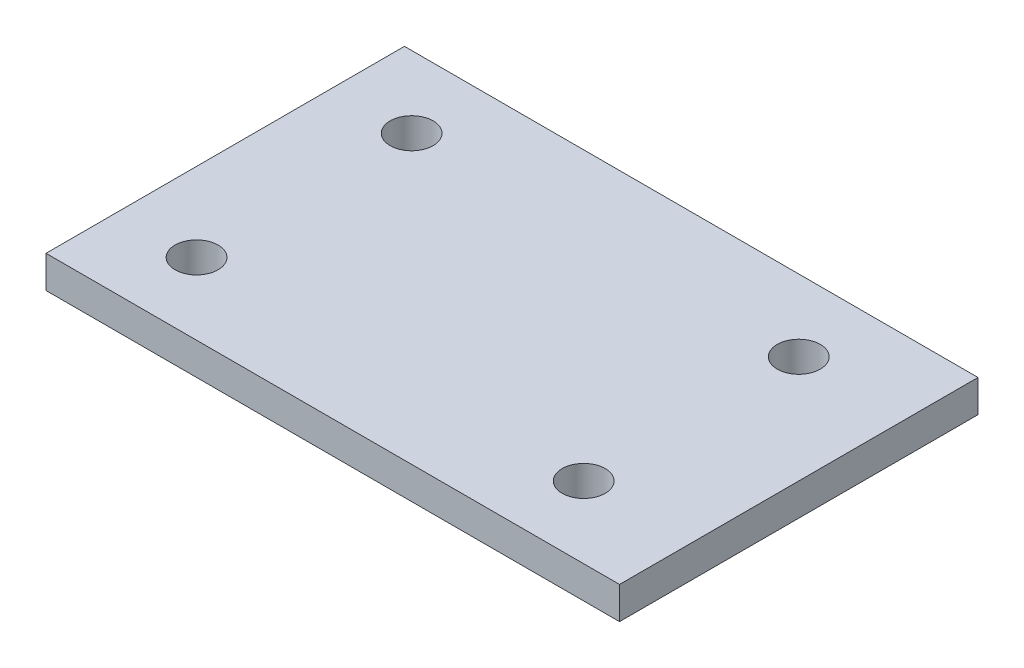
SolidWorks part; units mm, degrees
ref_plane "Front Plane" through (0, 0, 0) normal (0, 0, 1) x (1, 0, 0)
ref_plane "Top Plane" through (0, 0, 0) normal (0, 1, 0) x (1, 0, 0)
ref_plane "Right Plane" through (0, 0, 0) normal (1, 0, 0) x (0, 0, -1)
sketch "Sketch1" plane through (0, 0, 0) normal (0, 1, 0) x (1, 0, 0)
  line L1 (0, 0) -> (80, 0)
  line L2 (0, 0) -> (0, 50)
  line L3 (0, 50) -> (80, 50)
  line L4 (80, 0) -> (80, 50)
  dimension "D1" = 80
  dimension "D2" = 50
extrude "Boss-Extrude1" add sketch "Sketch1" along normal blind 4.5
sketch "Sketch2" plane through (0, 4.5, 0) normal (0, 1, 0) x (1, 0, 0)
  line L0 (80, 0) -> (80, 50) construction
  line L1 (80, 50) -> (0, 50) construction
  line L2 (0, 0) -> (80, 0) construction
  circle A0 centre (65, 40) radius 3
  circle A1 centre (65, 10) radius 3
  dimension "D1" = 6
  dimension "D5" = 6
  dimension "D2" = 15
  dimension "D3" = 10
  dimension "D4" = 10
extrude "Cut-Extrude1" cut sketch "Sketch2" against normal blind 4.5
sketch "Sketch3" plane through (0, 4.5, 0) normal (0, 1, 0) x (1, 0, 0)
  circle A0 centre (11, 40) radius 3
  circle A1 centre (11, 10) radius 3
extrude "Cut-Extrude2" cut sketch "Sketch3" against normal blind 10
